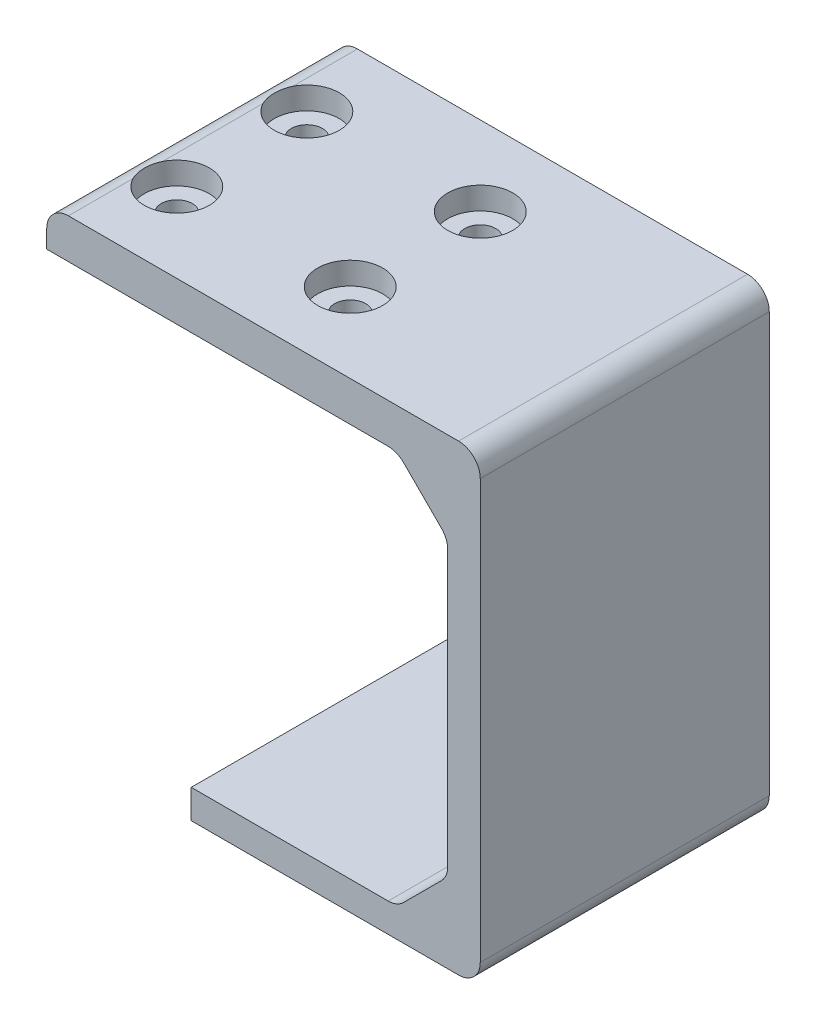
SolidWorks part; units mm, degrees
ref_plane "Front Plane" through (0, 0, 0) normal (0, 0, 1) x (1, 0, 0)
ref_plane "Top Plane" through (0, 0, 0) normal (0, 1, 0) x (1, 0, 0)
ref_plane "Right Plane" through (0, 0, 0) normal (1, 0, 0) x (0, 0, -1)
sketch "Sketch1" plane through (0, 0, 0) normal (0, 0, 1) x (1, 0, 0)
  line L0 (0, 32) -> (0, -32)
  line L1 (0, 32) -> (-60, 32)
  line L2 (-60, 32) -> (-60, 26.5)
  line L3 (-60, 26.5) -> (-4.5, 26.5)
  line L4 (-4.5, 26.5) -> (-4.5, -28)
  line L5 (-4.5, -28) -> (-40, -28)
  line L6 (-40, -28) -> (-40, -32)
  line L7 (-40, -32) -> (0, -32)
  point P4 (0, 0)
  dimension "D1" = 64
  dimension "D2" = 60
  dimension "D3" = 5.5
  dimension "D4" = 4
  dimension "D5" = 4.5
  dimension "D6" = 40
extrude "Boss-Extrude1" add sketch "Sketch1" along normal blind 40
ref_plane "Plane1" through (-4.5, 26.5, 40) normal (0, 0, -1) x (-1, 0, 0)
chamfer "Chamfer1" distance 7 angle 45 2 edges at (-4.5, -28, 20) (-4.5, 26.5, 20)
fillet "Fillet1" radius 3 7 edges at (0, -32, 20) (0, 32, 20) (-11.5, -28, 20) (-4.5, -21, 20) (-4.5, 19.5, 20) (-11.5, 26.5, 20) (-60, 32, 20)
sketch "Sketch2" plane through (0, 32, 0) normal (0, 1, 0) x (1, 0, 0)
  line L0 (-60, -40) -> (-60, 0) construction
  line L1 (-3, -40) -> (-57, -40) construction
  point P0 (-53, -29)
  point P1 (-53, -11)
  point P2 (-29, -11)
  point P3 (-29, -29)
  point P6 (0, 0)
  point P7 (0, 0)
  point P10 (0, 0)
  point P11 (0, 0)
  point P12 (0, 0)
  dimension "D1" = 7
  dimension "D2" = 24
  dimension "D3" = 11
  dimension "D4" = 18
hole_wizard "CBORE for M4 Pan Head Machine Screw1" positions "Sketch3" profile "Sketch4" counterbore size "M4" standard "ANSI Metric"
sketch "Sketch3" plane through (0, 32, 0) normal (0, 1, 0) x (1, 0, 0)
  point P0 (-53, -11)
  point P3 (-53, -29)
  point P6 (-29, -29)
  point P9 (-29, -11)
sketch "Sketch4" plane through (-53, 32, 11) normal (1, 0, 0) x (0, 0, 1)
  line L0 (0, 0) -> (0, 5.5)
  line L1 (0, 5.5) -> (2.15, 5.5)
  line L3 (2.15, 5.5) -> (2.15, 3.1)
  line L4 (2.15, 3.1) -> (4.5, 3.1)
  line L5 (4.5, 3.1) -> (4.5, 0)
  line L7 (4.5, 0) -> (0, 0)
  line L11 (0, -6.35) -> (0, 107.95) construction
  dimension "Thru Hole Dia." = 4.3
  dimension "Thru Hole Depth" = 5.5
  dimension "C'Bore Dia." = 9
  dimension "C'Bore Depth" = 3.1
